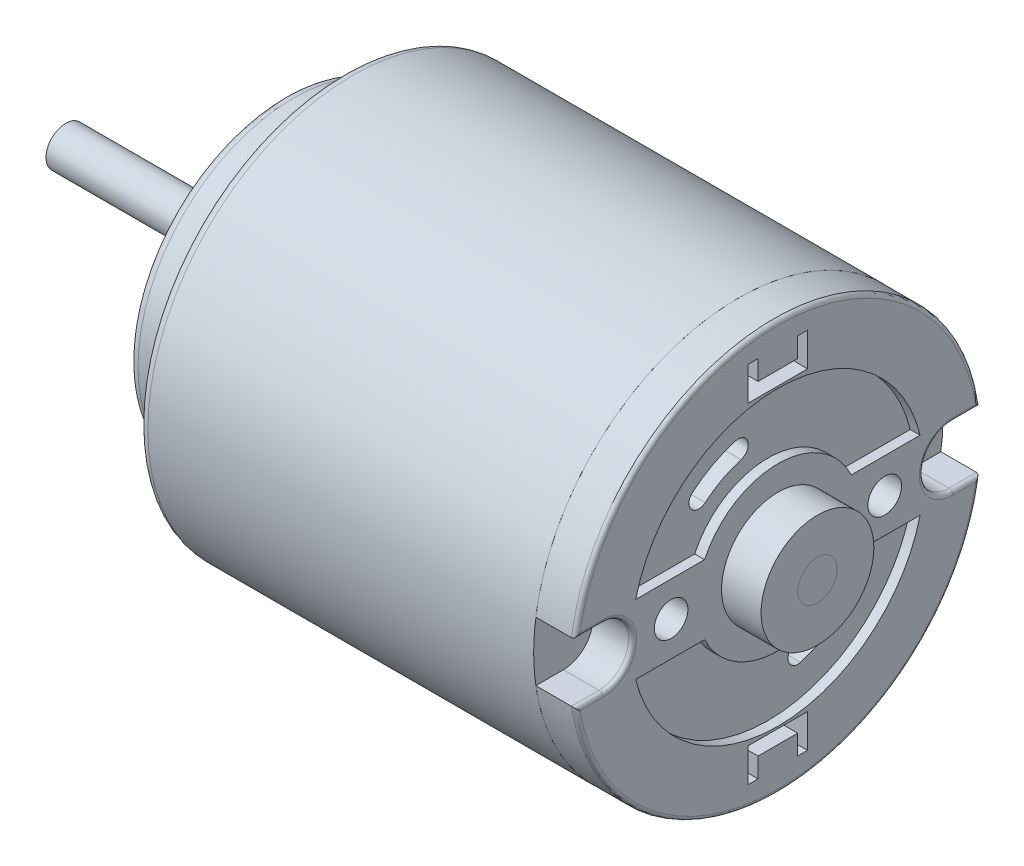
SolidWorks part; units mm, degrees
ref_plane "Front Plane" through (0, 0, 0) normal (0, 0, 1) x (1, 0, 0)
ref_plane "Top Plane" through (0, 0, 0) normal (0, 1, 0) x (1, 0, 0)
ref_plane "Right Plane" through (0, 0, 0) normal (1, 0, 0) x (0, 0, -1)
sketch "Sketch1" plane through (0, 0, 0) normal (1, 0, 0) x (0, 0, -1)
  circle A0 centre (0, 0) radius 10.35
  dimension "D1" = 20.7
extrude "Boss-Extrude1" add sketch "Sketch1" along normal blind 23
sketch "Sketch2" plane through (23, 0, 0) normal (1, 0, 0) x (0, 0, -1)
  circle A0 centre (0, 0) radius 2.85
  dimension "D1" = 5.7
extrude "Boss-Extrude2" add sketch "Sketch2" along normal blind 4
sketch "Sketch3" plane through (27, 0, 0) normal (1, 0, 0) x (0, 0, -1)
  circle A0 centre (0, 0) radius 1
  dimension "D1" = 2
extrude "Cut-Extrude1" cut sketch "Sketch3" against normal through all
sketch "Sketch4" plane through (0, 0, 0) normal (-1, 0, 0) x (0, 0, 1)
  circle A0 centre (0, 0) radius 7.85
  dimension "D1" = 15.7
extrude "Cut-Extrude2" cut sketch "Sketch4" against normal blind 3 flip side to cut
fillet "Fillet1" radius 0.5 3 edges at (3, 0, 7.85) (0, 0, 7.85) (3, 0, 10.35)
sketch "Sketch5" plane through (0, 0, 0) normal (-1, 0, 0) x (0, 0, 1)
  circle A0 centre (0, 0) radius 1 construction
  circle A1 centre (0, 0) radius 1
  circle A2 centre (0, 0) radius 3
  dimension "D1" = 6
extrude "Boss-Extrude3" add sketch "Sketch5" along normal blind 2
sketch "Sketch6" plane through (0, 0, 0) normal (-1, 0, 0) x (0, 0, 1)
  line L0 (0, 0) -> (5, 0) construction
  line L1 (0, 0) -> (-5, 0) construction
  circle A0 centre (5, 0) radius 1
  circle A1 centre (-5, 0) radius 1
  dimension "D1" = 2
  dimension "D2" = 2
  dimension "D3" = 10
  dimension "D4" = 5
extrude "Cut-Extrude3" cut sketch "Sketch6" against normal blind 3
sketch "Sketch7" plane through (23, 0, 0) normal (1, 0, 0) x (0, 0, -1)
  circle A0 centre (0, 0) radius 10.35 construction
  circle A1 centre (0, 0) radius 2.85 construction
  circle A2 centre (0, 0) radius 10.35
  circle A3 centre (0, 0) radius 2.85
extrude "Boss-Extrude4" add sketch "Sketch7" along normal blind 2 separate body
sketch "Sketch8" plane through (25, 0, 0) normal (1, 0, 0) x (0, 0, -1)
  line L0 (-8.85, 1.5) -> (-12.5844, 1.5)
  line L1 (-12.5844, 1.5) -> (-12.5844, -1.5)
  line L2 (-12.5844, -1.5) -> (-8.85, -1.5)
  line L3 (0, 0) -> (0, 8.85) construction
  line L4 (12.5844, -1.5) -> (8.85, -1.5)
  line L5 (12.5844, 1.5) -> (12.5844, -1.5)
  line L6 (8.85, 1.5) -> (12.5844, 1.5)
  circle A0 centre (0, 0) radius 8.85 construction
  arc A2 (-8.85, -1.5) -> (-8.85, 1.5) centre (-8.85, 0) ccw
  circle A3 centre (0, 0) radius 10.35 construction
  arc A4 (8.85, -1.5) -> (8.85, 1.5) centre (8.85, 0) cw
  dimension "D1" = 3
extrude "Cut-Extrude4" cut sketch "Sketch8" against normal blind 2
sketch "Sketch9" plane through (25, 0, 0) normal (1, 0, 0) x (0, 0, -1)
  circle A0 centre (0, 0) radius 5.4 construction
  circle A1 centre (-5.4, 0) radius 0.85
  circle A2 centre (5.4, 0) radius 0.85
  arc A3 (-1.5, 5.1875) -> (-3.5, 4.1122) centre (0, 0) ccw construction
  arc A4 (-1.6389, 5.6678) -> (-3.8241, 4.4929) centre (0, 0) ccw
  arc A5 (-1.3611, 4.7072) -> (-3.1759, 3.7314) centre (0, 0) ccw
  arc A6 (-1.3611, 4.7072) -> (-1.6389, 5.6678) centre (-1.5, 5.1875) ccw
  arc A7 (-3.8241, 4.4929) -> (-3.1759, 3.7314) centre (-3.5, 4.1122) ccw
  arc A8 (3.5, -4.1122) -> (1.5, -5.1875) centre (0, 0) cw construction
  arc A9 (1.6389, -5.6678) -> (3.8241, -4.4929) centre (0, 0) ccw
  arc A10 (1.3611, -4.7072) -> (3.1759, -3.7314) centre (0, 0) ccw
  arc A11 (1.3611, -4.7072) -> (1.6389, -5.6678) centre (1.5, -5.1875) ccw
  arc A12 (3.8241, -4.4929) -> (3.1759, -3.7314) centre (3.5, -4.1122) ccw
  point P9 (-2.5572, 4.7561)
  point P14 (2.5572, -4.7561)
  dimension "D1" = 1.7
  dimension "D2" = 1.7
  dimension "D3" = 1
  dimension "D4" = 1
  dimension "D5" = 10.8
  dimension "D6" = 1.5
  dimension "D7" = 3.5
  dimension "D8" = 1.5
  dimension "D9" = 3.5
extrude "Cut-Extrude5" cut sketch "Sketch9" against normal blind 2
sketch "Sketch10" plane through (25, 0, 0) normal (1, 0, 0) x (0, 0, -1)
  line L0 (-10.35, 0) -> (10.35, 0) construction
  line L1 (0, 0) -> (0, 10.35) construction
  line L2 (-1.5, 9.2) -> (-1.5, 7.5)
  line L3 (-1.5, 7.5) -> (1.5, 7.5)
  line L4 (-1.5, 9.2) -> (-1, 9.2)
  line L5 (-1, 9.2) -> (-1, 8.2)
  line L6 (-1, 8.2) -> (1, 8.2)
  line L7 (1.5, 9.2) -> (1.5, 7.5)
  line L8 (1.5, 9.2) -> (1, 9.2)
  line L9 (1, 9.2) -> (1, 8.2)
  line L16 (1.5, -9.2) -> (1.5, -7.5)
  line L17 (1.5, -9.2) -> (1, -9.2)
  line L18 (1, -9.2) -> (1, -8.2)
  line L19 (-1.5, -9.2) -> (-1.5, -7.5)
  line L20 (-1.5, -9.2) -> (-1, -9.2)
  line L21 (-1, -9.2) -> (-1, -8.2)
  line L25 (-1, -8.2) -> (1, -8.2)
  line L28 (-1.5, -7.5) -> (1.5, -7.5)
  circle A0 centre (0, 0) radius 10.35 construction
  arc A1 (10.2407, 1.5) -> (-10.2407, 1.5) centre (0, 0) ccw construction
  point P19 (0, 8.2)
  point P20 (0, 7.5)
  point P30 (0, -7.5)
  point P31 (0, -8.2)
  dimension "D1" = 1.5
  dimension "D2" = 0.5
  dimension "D3" = 1
  dimension "D4" = 7.5
  dimension "D5" = 1.7
extrude "Cut-Extrude6" cut sketch "Sketch10" against normal blind 2
fillet "Fillet2" radius 0.2 8 edges at (25, 1.5, -9.5454) (25, -1.5, -9.5454) (25, -1.5, 9.5454) (25, 1.5, 9.5454) (25, 0, -7.35) (25, 0, 7.35) (25, -10.35, 0) (25, 10.35, 0)
sketch "Sketch11" plane through (25, 0, 0) normal (1, 0, 0) x (0, 0, -1)
  line L0 (-7.2224, 1.75) -> (-3.2958, 1.75) construction
  line L1 (-3.2958, 1.75) -> (-3.2958, -1.75) construction
  line L2 (-3.2958, -1.75) -> (-7.2224, -1.75) construction
  line L3 (-7.2224, -1.75) -> (-7.2224, 1.75) construction
  line L4 (0, 0) -> (-3.2958, 0) construction
  line L5 (-7.1901, 1.75) -> (-3.7078, 1.75)
  line L6 (0, 7.4) -> (0, 0) construction
  line L8 (7.1901, 1.75) -> (3.7078, 1.75)
  line L9 (-7.2224, -1.75) -> (-3.2958, -1.75) construction
  line L10 (7.1901, -1.75) -> (3.7078, -1.75)
  line L11 (-7.1901, -1.75) -> (-3.7078, -1.75)
  arc A0 (3.7078, 1.75) -> (-3.7078, 1.75) centre (0, 0) ccw
  arc A1 (7.1901, 1.75) -> (-7.1901, 1.75) centre (0, 0) ccw
  arc A2 (7.1901, -1.75) -> (-7.1901, -1.75) centre (0, 0) cw
  arc A3 (3.7078, -1.75) -> (-3.7078, -1.75) centre (0, 0) cw
  dimension "D3" = 3.3
  dimension "D1" = 3.5
extrude "Cut-Extrude7" cut sketch "Sketch11" against normal blind 0.5
sketch "Sketch12" plane through (27, 0, 0) normal (1, 0, 0) x (0, 0, -1)
  circle A0 centre (0, 0) radius 1
  dimension "D1" = 2
extrude "Boss-Extrude5" add sketch "Sketch12" against normal offset from surface (38 mm away) 9 separate body up to face at (-2, 0, 3) offset beyond the face yes
